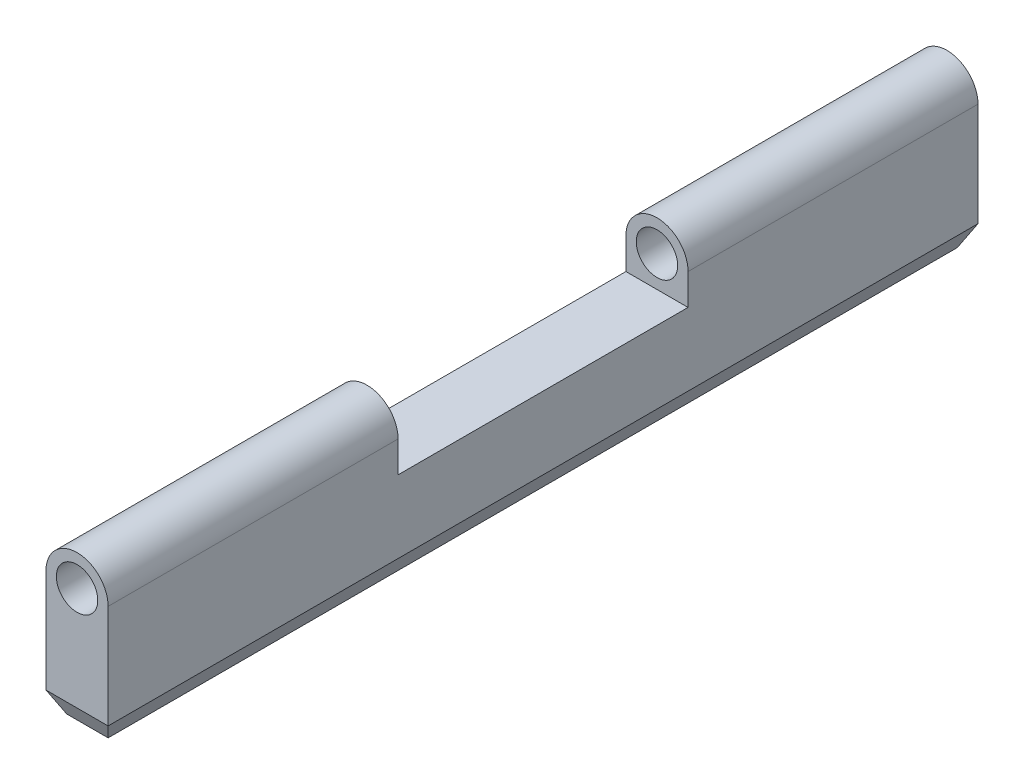
SolidWorks part; units mm, degrees
ref_plane "Front Plane" through (0, 0, 0) normal (0, 0, 1) x (1, 0, 0)
ref_plane "Top Plane" through (0, 0, 0) normal (0, 1, 0) x (1, 0, 0)
ref_plane "Right Plane" through (0, 0, 0) normal (1, 0, 0) x (0, 0, -1)
sketch "Sketch1" plane through (0, 0, 0) normal (0, 0, 1) x (1, 0, 0)
  line L0 (-1.5, 2.8712) -> (-1.5, -3.1288)
  line L1 (-1.5, -3.1288) -> (1.5, -3.1288)
  line L2 (1.5, -3.1288) -> (1.5, 2.8712)
  circle A0 centre (0, 2.8712) radius 1
  arc A1 (-1.5, 2.8712) -> (1.5, 2.8712) centre (0, 2.8712) cw
  point P7 (0, -3.1288)
  dimension "D1" = 2
  dimension "D2" = 3
  dimension "D3" = 6
extrude "Boss-Extrude1" add sketch "Sketch1" along normal blind 42
sketch "Sketch2" plane through (0, 0, 0) normal (1, 0, 0) x (0, 0, -1)
  line L0 (0, 4.3712) -> (-42, 4.3712) construction
  line L1 (-14, 4.3712) -> (-28, 4.3712)
  line L2 (-14, 4.3712) -> (-14, 1.3712)
  line L3 (-14, 1.3712) -> (-28, 1.3712)
  line L4 (-28, 4.3712) -> (-28, 1.3712)
  line L5 (-42, 4.3712) -> (0, 4.3712) construction
  point P6 (-21, 4.3712)
  point P11 (-21, 4.3712)
  dimension "D1" = 14
  dimension "D2" = 3
extrude "Cut-Extrude1" cut sketch "Sketch2" against normal through all both and the other way through all
chamfer "Chamfer1" distance 0.5 distance2 1 4 edges at (0, -3.1288, 0) (-1.5, -3.1288, 21) (0, -3.1288, 42) (1.5, -3.1288, 21)
equation "\"0.510.00mm\"=785.398"
